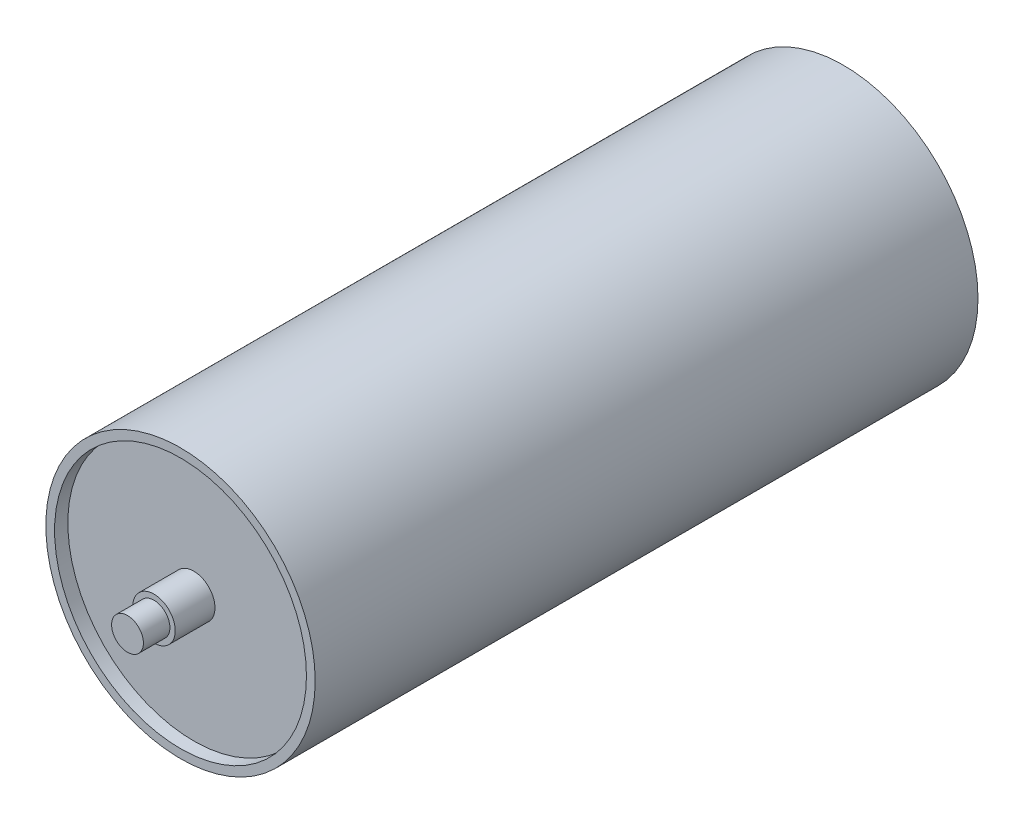
SolidWorks part; units mm, degrees
material "AISI 1010 Steel, hot rolled bar"
ref_plane "Front Plane" through (0, 0, 0) normal (0, 0, 1) x (1, 0, 0)
ref_plane "Top Plane" through (0, 0, 0) normal (0, 1, 0) x (1, 0, 0)
ref_plane "Right Plane" through (0, 0, 0) normal (1, 0, 0) x (0, 0, -1)
sketch "Sketch1" plane through (0, 0, 0) normal (0, 0, 1) x (1, 0, 0)
  circle A0 centre (0, 0) radius 50.8
  dimension "D1" = 101.6
extrude "Boss-Extrude1" add sketch "Sketch1" along normal blind 250
sketch "Sketch2" plane through (0, 0, 250) normal (0, 0, 1) x (1, 0, 0)
  circle A0 centre (0, 0) radius 47.5
  dimension "D1" = 95
extrude "Cut-Extrude1" cut sketch "Sketch2" against normal blind 5
sketch "Sketch3" plane through (0, 0, 0) normal (0, 0, -1) x (-1, 0, 0)
  circle A0 centre (0, 0) radius 47.5
  dimension "D1" = 95
extrude "Cut-Extrude2" cut sketch "Sketch3" against normal blind 5
sketch "Sketch4" plane through (0, 0, 5) normal (0, 0, -1) x (-1, 0, 0)
  circle A0 centre (0, 0) radius 8
extrude "Boss-Extrude2" add sketch "Sketch4" along normal blind 15
sketch "Sketch5" plane through (0, 0, 245) normal (0, 0, 1) x (1, 0, 0)
  circle A0 centre (0, 0) radius 8
extrude "Boss-Extrude3" add sketch "Sketch5" along normal blind 15
sketch "Sketch7" plane through (0, 0, -10) normal (0, 0, -1) x (-1, 0, 0)
  circle A0 centre (0, 0) radius 6
extrude "Boss-Extrude4" add sketch "Sketch7" along normal blind 10
sketch "Sketch8" plane through (0, 0, 260) normal (0, 0, 1) x (1, 0, 0)
  circle A0 centre (0, 0) radius 6
extrude "Boss-Extrude5" add sketch "Sketch8" along normal blind 10
